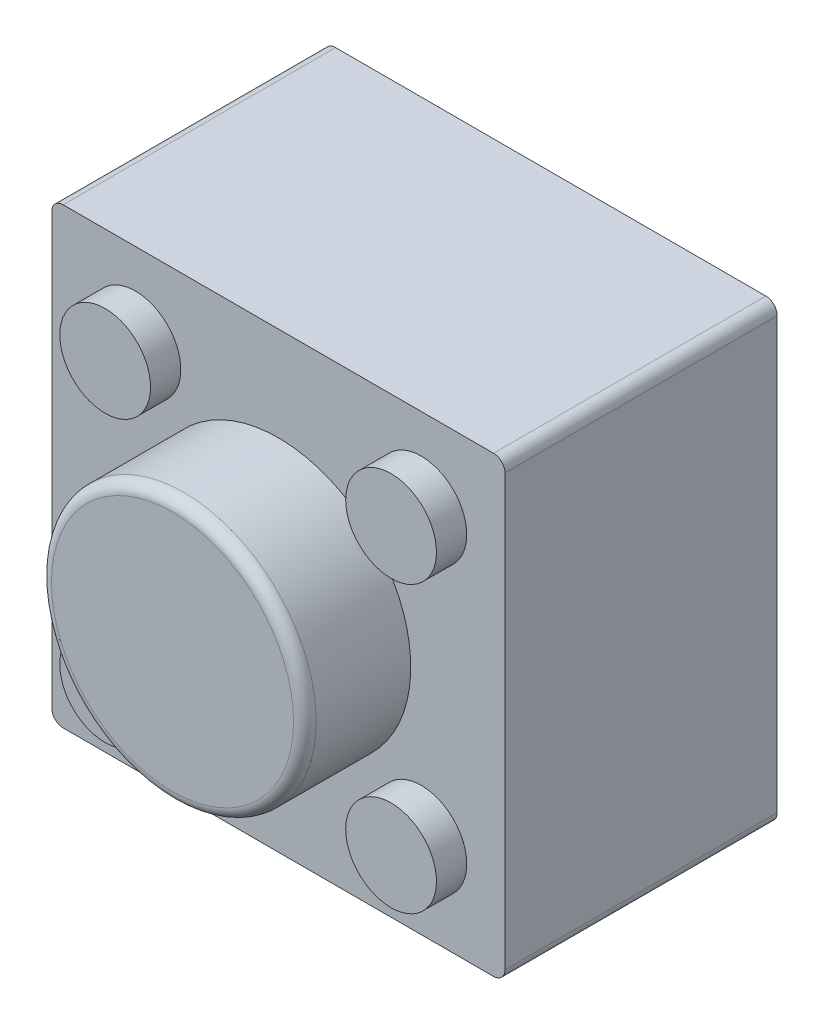
SolidWorks part; units mm, degrees
ref_plane "Front Plane" through (0, 0, 0) normal (0, 0, 1) x (1, 0, 0)
ref_plane "Top Plane" through (0, 0, 0) normal (0, 1, 0) x (1, 0, 0)
ref_plane "Right Plane" through (0, 0, 0) normal (1, 0, 0) x (0, 0, -1)
sketch "Sketch2" plane through (0, 0, 0) normal (0, 0, 1) x (1, 0, 0)
  line L1 (0, 0) -> (5.99, 0)
  line L2 (0, 0) -> (0, 5.99)
  line L3 (0, 5.99) -> (5.99, 5.99)
  line L4 (5.99, 0) -> (5.99, 5.99)
  dimension "D1" = 5.99
  dimension "D2" = 5.99
extrude "Boss-Extrude1" add sketch "Sketch2" along normal blind 3.6
sketch "Sketch3" plane through (0, 0, 3.6) normal (0, 0, 1) x (1, 0, 0)
  line L0 (2.995, 5.99) -> (2.995, 0) construction
  line L1 (5.99, 5.99) -> (0, 5.99) construction
  line L2 (0, 0) -> (5.99, 0) construction
  line L4 (0, 5.99) -> (0, 0) construction
  line L5 (0, 2.995) -> (5.99, 2.995) construction
  line L6 (5.99, 0) -> (5.99, 5.99) construction
  circle A0 centre (2.995, 2.995) radius 1.75
  dimension "D1" = 3.5
extrude "Boss-Extrude2" add sketch "Sketch3" along normal blind 1.4
ref_plane "Plane1" through (0, 2.995, 0) normal (0, 1, 0) x (1, 0, 0)
ref_plane "Plane2" through (2.995, 0, 0) normal (1, 0, 0) x (0, 0, -1)
ref_plane "Plane3" through (5.24, 0, 0) normal (1, 0, 0) x (0, 0, -1)
fillet "Fillet1" radius 0.15 5 edges at (4.745, 2.995, 5) (0, 0, 1.8) (0, 5.99, 1.8) (5.99, 5.99, 1.8) (5.99, 0, 1.8)
sketch "Sketch5" plane through (0, 0, 3.6) normal (0, 0, 1) x (1, 0, 0)
  line L0 (1.105, 5.99) -> (1.105, 0) construction
  line L1 (5.84, 5.99) -> (0.15, 5.99) construction
  line L2 (4.885, 5.99) -> (4.885, 0) construction
  line L3 (0.15, 0) -> (5.84, 0) construction
  line L4 (5.99, 0.15) -> (5.99, 5.84) construction
  line L5 (5.99, 1.11) -> (0, 1.11) construction
  line L6 (0, 5.84) -> (0, 0.15) construction
  line L8 (5.99, 4.88) -> (0, 4.88) construction
  circle A0 centre (1.105, 4.88) radius 0.6
  circle A1 centre (4.885, 4.88) radius 0.6
  circle A2 centre (4.885, 1.11) radius 0.6
  circle A3 centre (1.105, 1.11) radius 0.6
  point P28 (0, 0)
  point P29 (0, 0)
  point P30 (0, 0)
  point P31 (0, 0)
  dimension "D3" = 1.2
  dimension "D1" = 1.11
  dimension "D2" = 1.11
  dimension "D4" = 1.105
  dimension "D5" = 1.105
extrude "Boss-Extrude3" add sketch "Sketch5" along normal blind 0.4
